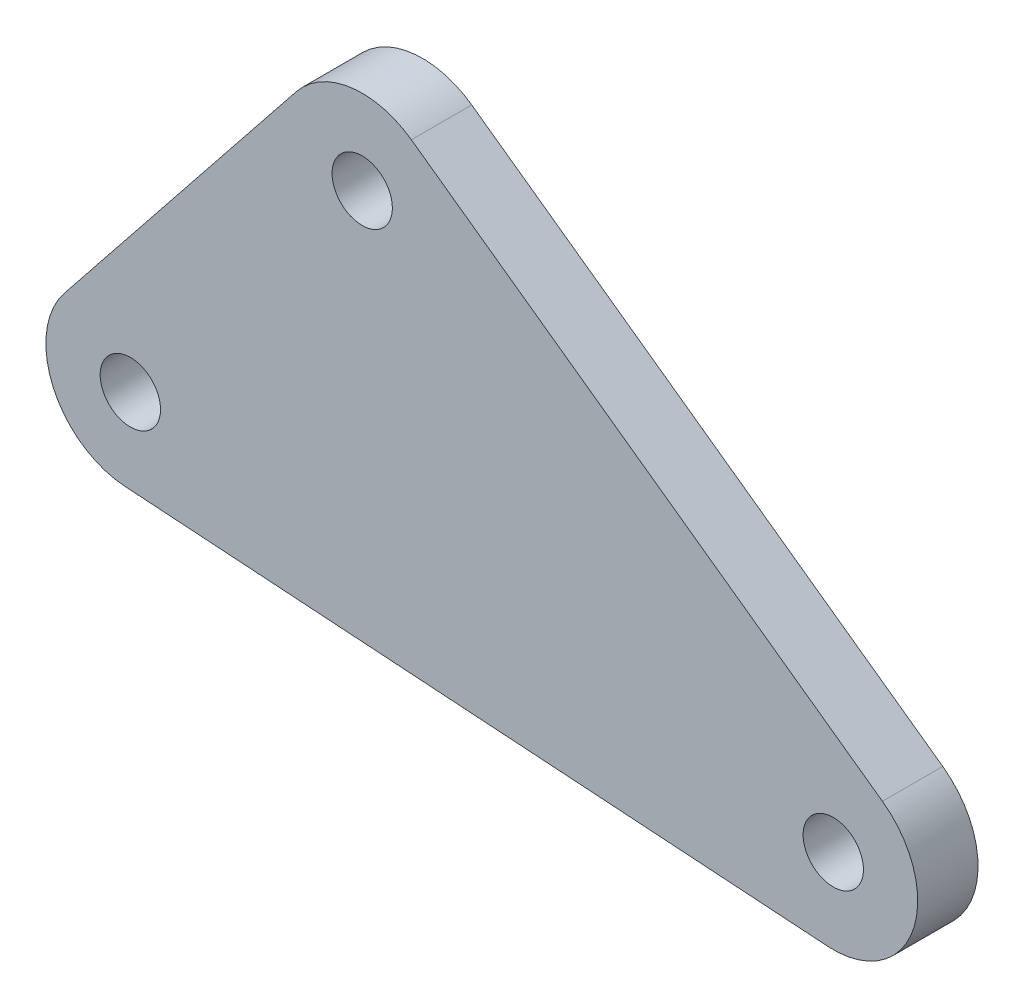
SolidWorks part; units mm, degrees
ref_plane "Front Plane" through (0, 0, 0) normal (0, 0, 1) x (1, 0, 0)
ref_plane "Top Plane" through (0, 0, 0) normal (0, 1, 0) x (1, 0, 0)
ref_plane "Right Plane" through (0, 0, 0) normal (1, 0, 0) x (0, 0, -1)
sketch "Sketch1" plane through (0, 0, 0) normal (0, 0, 1) x (1, 0, 0)
  line L1 (0, 0) -> (24.4046, 30.5693) construction
  line L7 (24.4046, 30.5693) -> (73.9863, -4.9387) construction
  line L8 (73.9863, -4.9387) -> (0, 0) construction
  line L9 (-17.5531, -7.7381) -> (22.721, 42.7095)
  line L10 (22.721, 42.7095) -> (104.5445, -15.8883)
  line L11 (104.5445, -15.8883) -> (-17.5531, -7.7381)
  circle A0 centre (24.4046, 30.5693) radius 3.175
  circle A1 centre (0, 0) radius 3.175
  circle A2 centre (73.9863, -4.9387) radius 3.175
  dimension "D3" = 39.116
  dimension "D4" = 6.35
  dimension "D1" = 74.151
  dimension "D2" = 60.985
  dimension "D5" = 8.89
extrude "Boss-Extrude1" add sketch "Sketch1" along normal blind 6.35
fillet "Fillet1" radius 8.89 3 edges at (104.5445, -15.8883, 3.175) (-17.5531, -7.7381, 3.175) (22.721, 42.7095, 3.175)
